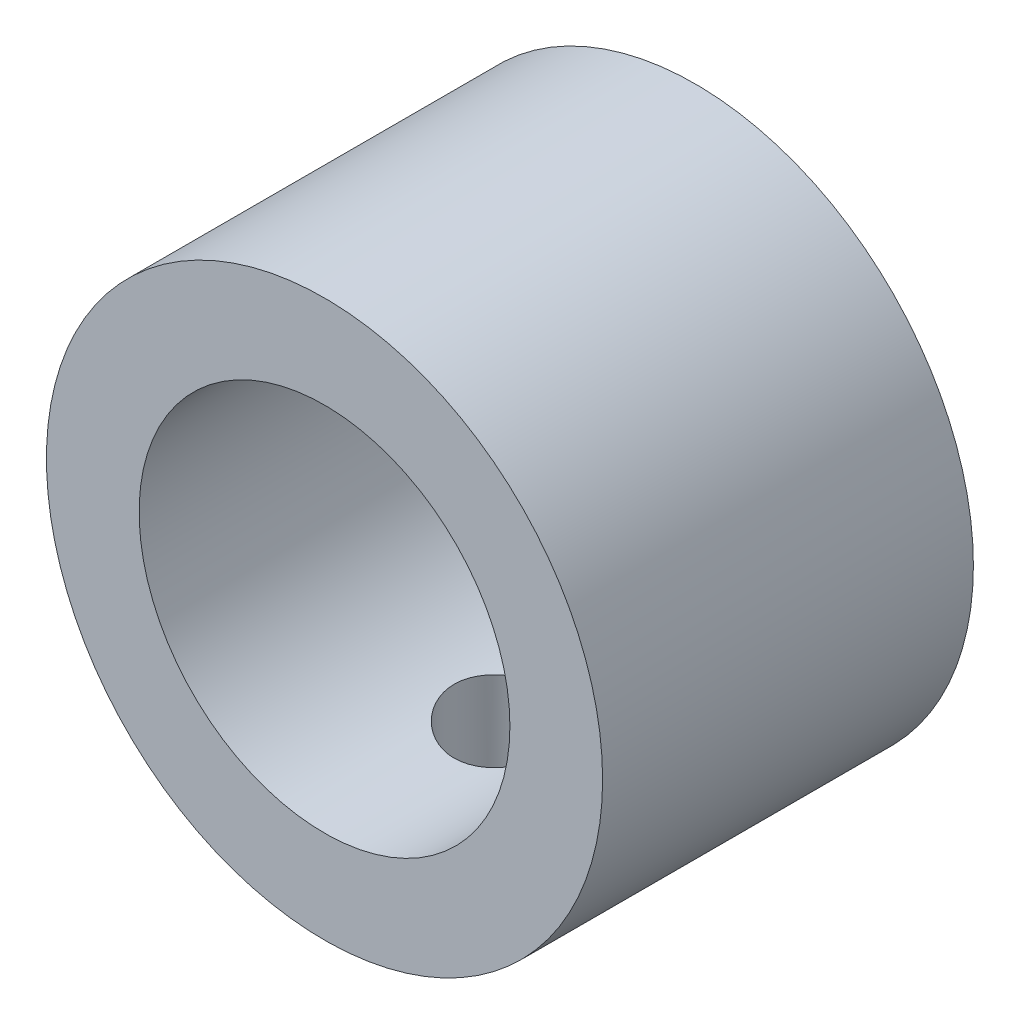
SolidWorks part; units mm, degrees
ref_plane "Front Plane" through (0, 0, 0) normal (0, 0, 1) x (1, 0, 0)
ref_plane "Top Plane" through (0, 0, 0) normal (0, 1, 0) x (1, 0, 0)
ref_plane "Right Plane" through (0, 0, 0) normal (1, 0, 0) x (0, 0, -1)
sketch "Sketch1" plane through (0, 0, 0) normal (0, 0, 1) x (1, 0, 0)
  circle A0 centre (0, 0) radius 5
  circle A1 centre (0, 0) radius 7.5
  dimension "D1" = 10
  dimension "D2" = 15
extrude "Boss-Extrude1" add sketch "Sketch1" along normal mid plane 10
sketch "Sketch3" plane through (0, 0, 0) normal (0, 1, 0) x (1, 0, 0)
  circle A0 centre (0, 0) radius 1.5
  dimension "D1" = 3
extrude "Cut-Extrude1" cut sketch "Sketch3" against normal through all
